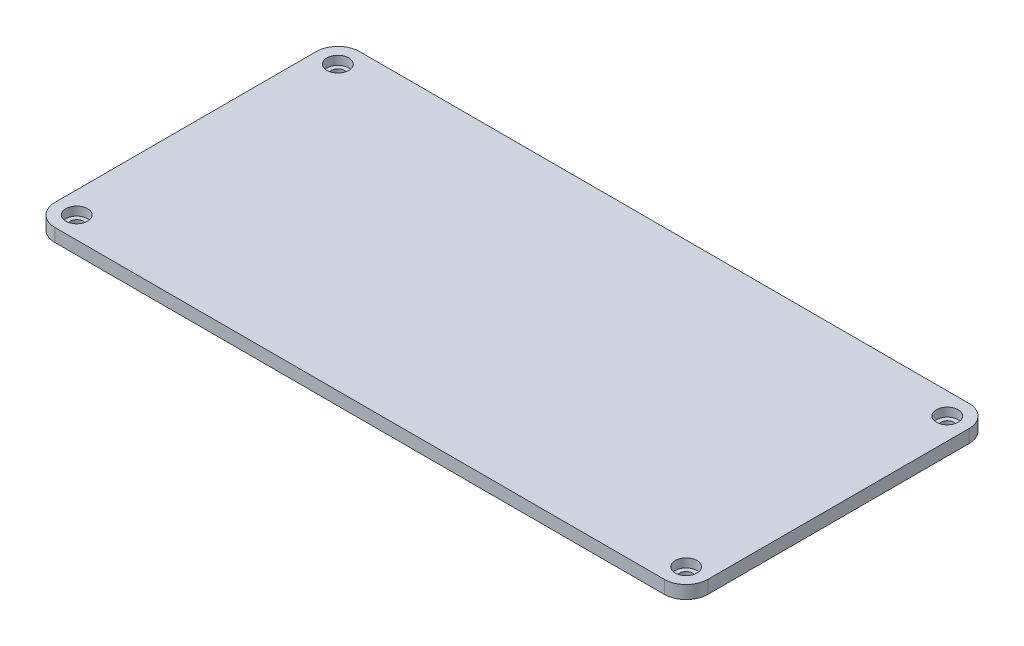
SolidWorks part; units mm, degrees
ref_plane "Спереди" through (0, 0, 0) normal (0, 0, 1) x (1, 0, 0)
ref_plane "Сверху" through (0, 0, 0) normal (0, 1, 0) x (1, 0, 0)
ref_plane "Справа" through (0, 0, 0) normal (1, 0, 0) x (0, 0, -1)
sketch "Эскиз1" plane through (0, 0, 0) normal (0, 1, 0) x (1, 0, 0)
  line L0 (-1000, 0) -> (49000, 0) construction
  line L1 (0, -1000) -> (0, 49000) construction
  line L2 (75, -35) -> (75, 35)
  line L3 (-75, -35) -> (-75, 35)
  line L4 (-75, -35) -> (75, -35)
  line L5 (-75, 35) -> (75, 35)
  line L7 (-1000, 35) -> (49000, 35) construction
  line L8 (-1000, -35) -> (49000, -35) construction
  line L9 (-75, -1000) -> (-75, 49000) construction
  line L10 (75, -1000) -> (75, 49000) construction
  dimension "D1" = 75
  dimension "D2" = 75
extrude "Бобышка-Вытянуть1" add sketch "Эскиз1" along normal blind 3
fillet "Скругление1" radius 5 4 edges at (75, 1.5, -35) (-75, 1.5, -35) (75, 1.5, 35) (-75, 1.5, 35)
sketch "Эскиз2" plane through (0, 3, 0) normal (0, 1, 0) x (1, 0, 0)
  circle A0 centre (-70, 30) radius 1.5
  circle A1 centre (70, 30) radius 1.5
  circle A2 centre (70, -30) radius 1.5
  circle A3 centre (-70, -30) radius 1.5
extrude "Вырез-Вытянуть1" cut sketch "Эскиз2" against normal blind 3
sketch "Эскиз3" plane through (0, 3, 0) normal (0, 1, 0) x (1, 0, 0)
  circle A0 centre (-70, 30) radius 2.5
  circle A1 centre (70, 30) radius 2.5
  circle A2 centre (70, -30) radius 2.5
  circle A3 centre (-70, -30) radius 2.5
extrude "Вырез-Вытянуть2" cut sketch "Эскиз3" against normal blind 2
sketch "Эскиз4" plane through (0, 0, 0) normal (0, -1, 0) x (1, 0, 0)
  line L2 (-72, -15) -> (-72, 15)
  line L4 (-30, -29) -> (30, -29)
  line L6 (69, -15) -> (69, 15)
  line L8 (-1000, 15) -> (49000, 15) construction
  line L10 (-30, -32) -> (30, -32)
  line L12 (0, -1000) -> (0, 49000) construction
  line L13 (-1000, 0) -> (49000, 0) construction
  line L14 (-72, -15) -> (-69, -15)
  line L15 (-72, 15) -> (-69, 15)
  line L16 (30, -32) -> (30, -29)
  line L17 (-30, -32) -> (-30, -29)
  line L18 (-30, 32) -> (30, 32)
  line L19 (-30, 29) -> (30, 29)
  line L20 (-1000, -15) -> (49000, -15) construction
  line L21 (-30, 29) -> (-30, 32)
  line L22 (-69, -15) -> (-69, 15)
  line L23 (-30, -1000) -> (-30, 49000) construction
  line L24 (30, 29) -> (30, 32)
  line L26 (30, -1000) -> (30, 49000) construction
  line L28 (69, -15) -> (72, -15)
  line L29 (72, -15) -> (72, 15)
  line L31 (69, 15) -> (72, 15)
  line L33 (-1045.9197, -29) -> (48954.0803, -29) construction
  line L34 (-1045.9197, -32) -> (48954.0803, -32) construction
  point P0 (-69, -991.3999)
  point P1 (-69, 49008.6001)
  point P2 (-1051.9161, 29)
  point P3 (48948.0839, 29)
  point P6 (69, -990.9265)
  point P7 (-1051.9161, 32)
  point P8 (69, 49009.0735)
  point P9 (48948.0839, 32)
  point P10 (-72, -991.3999)
  point P11 (-72, 49008.6001)
  point P14 (72, -990.9265)
  point P15 (72, 49009.0735)
  dimension "D2" = 3
  dimension "D3" = 15
  dimension "D4" = 15
  dimension "D5" = 30
  dimension "D6" = 30
extrude "Бобышка-Вытянуть2" add sketch "Эскиз4" along normal blind 2
